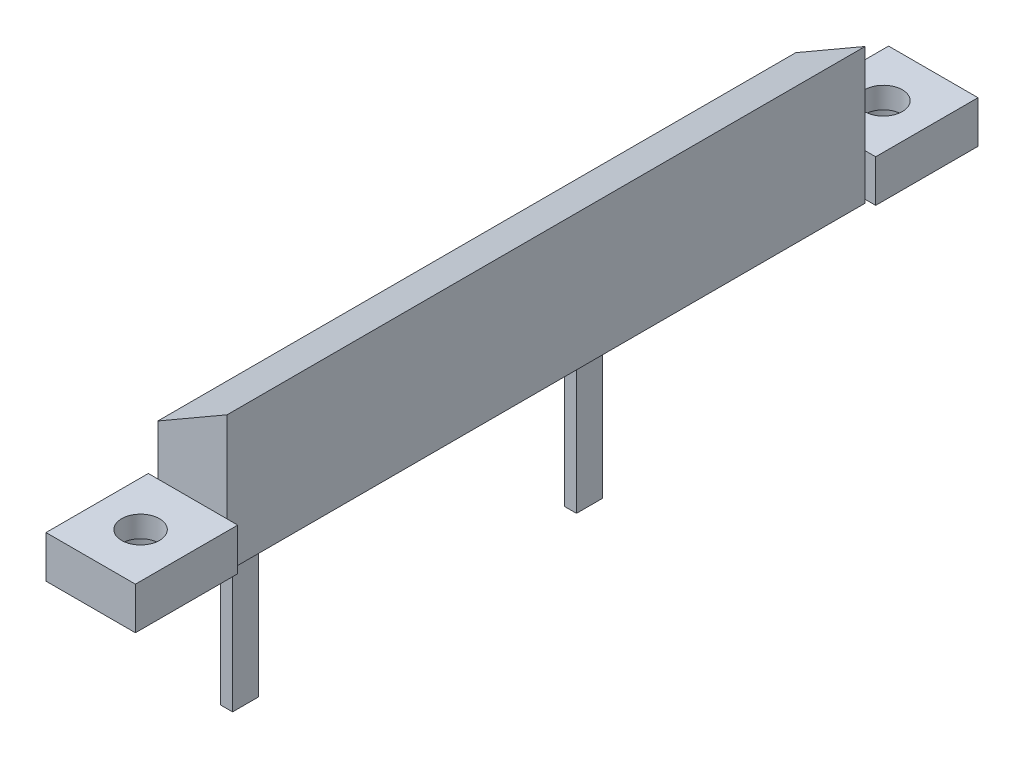
SolidWorks part; units mm, degrees
ref_plane "Front Plane" through (0, 0, 0) normal (0, 0, 1) x (1, 0, 0)
ref_plane "Top Plane" through (0, 0, 0) normal (0, 1, 0) x (1, 0, 0)
ref_plane "Right Plane" through (0, 0, 0) normal (1, 0, 0) x (0, 0, -1)
other "Configuration Table"
sketch "Sketch1" plane through (0, 0, 0) normal (0, 0, 1) x (1, 0, 0)
  line L0 (-17.3973, 18.8) -> (-13.3671, 18.8)
  line L1 (-13.3671, 18.8) -> (-13.3671, 26.6969)
  line L2 (-13.3671, 26.6969) -> (-17.3973, 24.3701)
  line L3 (-17.3973, 24.3701) -> (-17.3973, 18.8)
extrude "Clamp -X cover" add sketch "Sketch1" along normal blind 37.1 from offset 20.15
sketch "Sketch2" plane through (0, 0, 0) normal (0, 0, 1) x (1, 0, 0)
  line L0 (-17.95, 19) -> (-12.75, 19)
  line L1 (-12.75, 19) -> (-12.75, 21.45)
  line L2 (-12.75, 21.45) -> (-17.95, 21.45)
  line L3 (-17.95, 21.45) -> (-17.95, 19)
extrude "Ear -X cover -26" add sketch "Sketch2" along normal blind 5.95 from offset 26.1
sketch "Sketch3" plane through (0, 0, 0) normal (0, 0, 1) x (1, 0, 0)
  line L0 (-17.95, 19) -> (-12.75, 19)
  line L1 (-12.75, 19) -> (-12.75, 21.45)
  line L2 (-12.75, 21.45) -> (-17.95, 21.45)
  line L3 (-17.95, 21.45) -> (-17.95, 19)
extrude "Ear -X cover 17" add sketch "Sketch3" along normal blind 5.95 from offset 16.95
sketch "Sketch4" plane through (0, 0, 0) normal (0, 1, 0) x (1, 0, 0)
  circle A0 centre (-15.35, 23.2) radius 1.1
  circle A1 centre (-15.35, -20) radius 1.1
extrude "Cut-Extrude1" cut sketch "Sketch4" along normal blind 2.65 from offset 18.9
sketch "Sketch5" plane through (0, 0, 0) normal (0, 1, 0) x (1, 0, 0)
  circle A0 centre (-15.35, 23.2) radius 2
  circle A1 centre (-15.35, -20) radius 2
extrude "Cut-Extrude2" cut sketch "Sketch5" along normal blind 1.22 from offset 18.99
sketch "Sketch6" plane through (0, 0, 0) normal (0, 1, 0) x (1, 0, 0)
  line L1 (-17.95, 8.75) -> (-17.25, 8.75)
  line L2 (-17.95, 8.75) -> (-17.95, 7.25)
  line L3 (-17.95, 7.25) -> (-17.25, 7.25)
  line L4 (-17.25, 8.75) -> (-17.25, 7.25)
extrude "Boss-Extrude4" add sketch "Sketch6" along normal blind 11.11 from offset 7.69
sketch "Sketch7" plane through (0, 0, 0) normal (0, 1, 0) x (1, 0, 0)
  line L1 (-17.95, -11.25) -> (-17.25, -11.25)
  line L2 (-17.95, -11.25) -> (-17.95, -12.75)
  line L3 (-17.95, -12.75) -> (-17.25, -12.75)
  line L4 (-17.25, -11.25) -> (-17.25, -12.75)
extrude "Boss-Extrude5" add sketch "Sketch7" along normal blind 11.11 from offset 7.69
